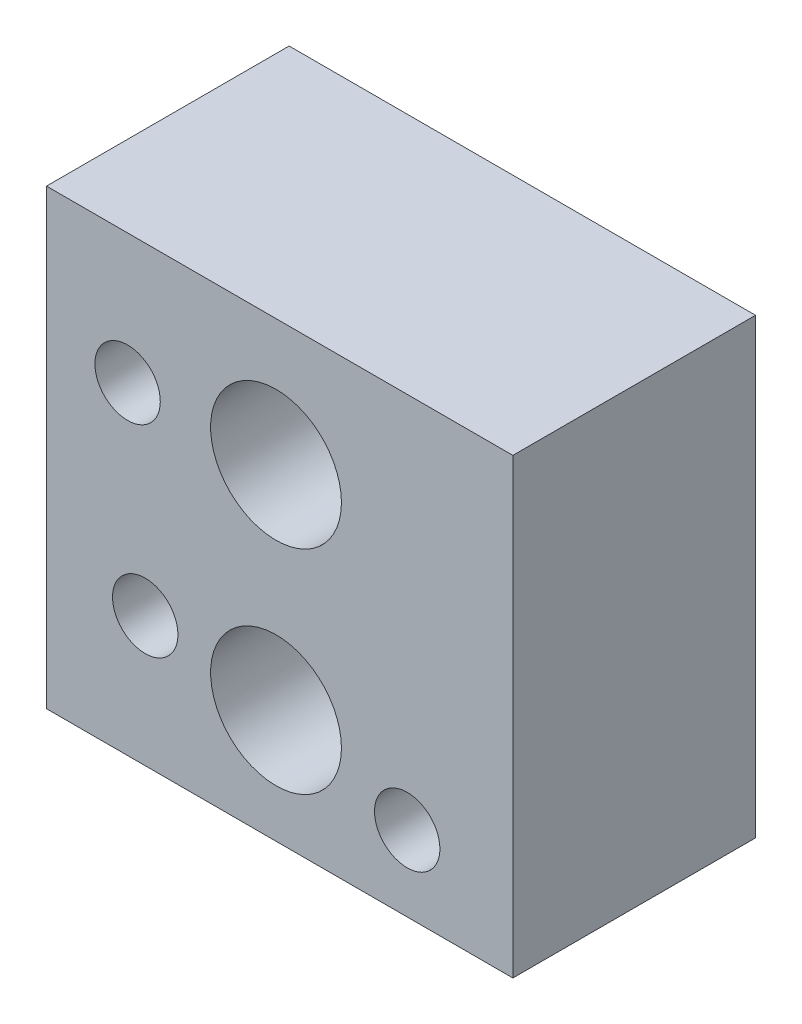
SolidWorks part; units mm, degrees
ref_plane "Front Plane" through (0, 0, 0) normal (0, 0, 1) x (1, 0, 0)
ref_plane "Top Plane" through (0, 0, 0) normal (0, 1, 0) x (1, 0, 0)
ref_plane "Right Plane" through (0, 0, 0) normal (1, 0, 0) x (0, 0, -1)
other "Configuration Table"
sketch "Sketch1" plane through (0, 0, 0) normal (0, 0, 1) x (1, 0, 0)
  line L1 (-101.8429, 80.9102) -> (79.2772, 80.9102)
  line L2 (-101.8429, 80.9102) -> (-101.8429, -94.8654)
  line L3 (-101.8429, -94.8654) -> (79.2772, -94.8654)
  line L4 (79.2772, 80.9102) -> (79.2772, -94.8654)
extrude "Extrude1" add sketch "Sketch1" along normal blind 94.234
sketch "Sketch2" plane through (0, 0, 94.234) normal (0, 0, 1) x (1, 0, 0)
  circle A0 centre (-70.3467, 30.5419) radius 12.7
  circle A1 centre (38.2469, -65.6338) radius 12.7
  circle A2 centre (-63.5, -44.45) radius 12.7
  circle A3 centre (-12.7, 31.75) radius 25.4
  circle A4 centre (-12.7, -50.8) radius 25.4
  dimension "D1" = 50.8
  dimension "D2" = 50.8
  dimension "D3" = 25.4
  dimension "D4" = 25.4
  dimension "D5" = 25.4
extrude "Extrude2" cut sketch "Sketch2" against normal through all
